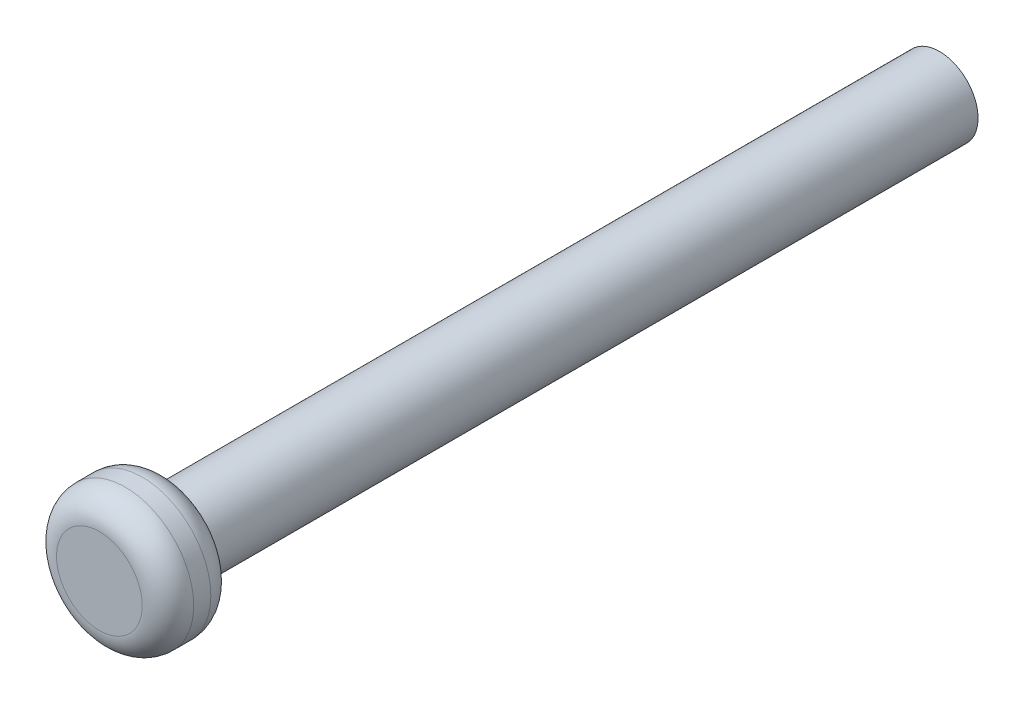
SolidWorks part; units mm, degrees
ref_plane "Front Plane" through (0, 0, 0) normal (0, 0, 1) x (1, 0, 0)
ref_plane "Top Plane" through (0, 0, 0) normal (0, 1, 0) x (1, 0, 0)
ref_plane "Right Plane" through (0, 0, 0) normal (1, 0, 0) x (0, 0, -1)
sketch "Sketch1" plane through (0, 0, 0) normal (0, 0, 1) x (1, 0, 0)
  circle A0 centre (0, 0) radius 2.25
  dimension "D1" = 4.5
extrude "Boss-Extrude1" add sketch "Sketch1" along normal blind 45
sketch "Sketch2" plane through (0, 0, 45) normal (0, 0, 1) x (1, 0, 0)
  circle A0 centre (0, 0) radius 4
  dimension "D1" = 8
extrude "Boss-Extrude2" add sketch "Sketch2" along normal blind 4
fillet "Fillet1" radius 1.5 2 edges at (4, 0, 45) (4, 0, 49)
